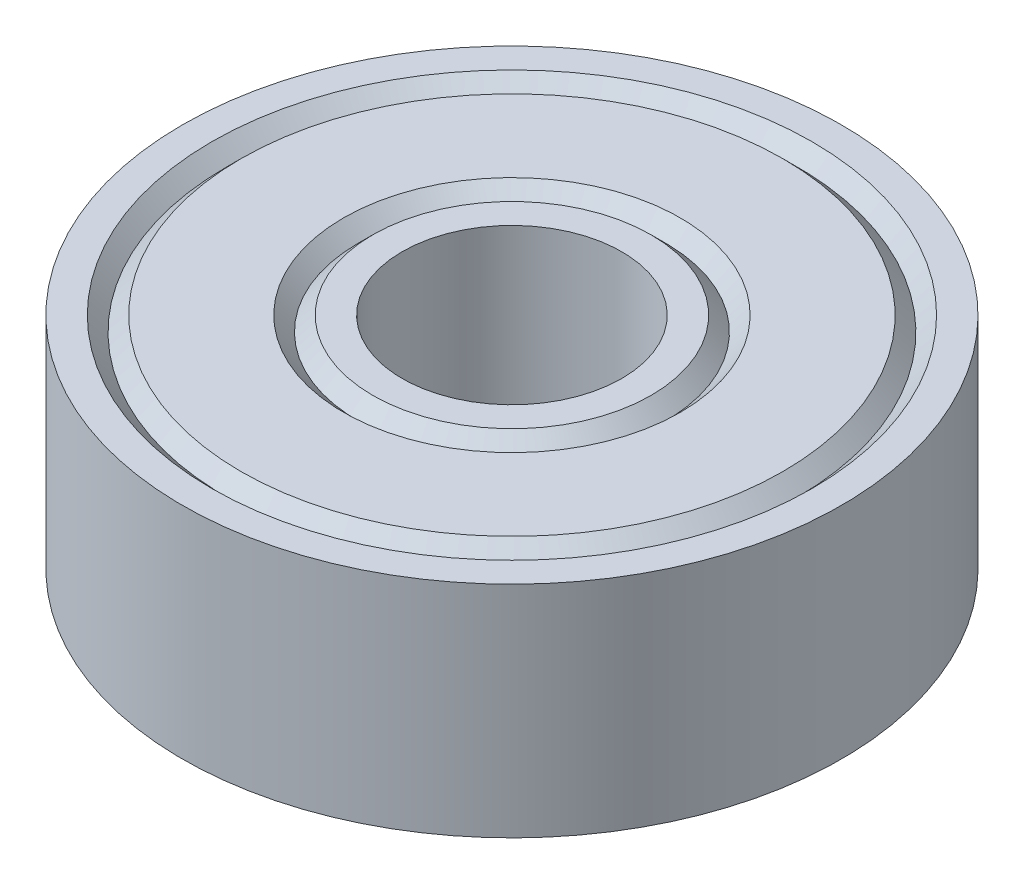
SolidWorks part; units mm, degrees
ref_plane "Front Plane" through (0, 0, 0) normal (0, 0, 1) x (1, 0, 0)
ref_plane "Top Plane" through (0, 0, 0) normal (0, 1, 0) x (1, 0, 0)
ref_plane "Right Plane" through (0, 0, 0) normal (1, 0, 0) x (0, 0, -1)
sketch "Sketch1" plane through (0, 0, 0) normal (0, 0, 1) x (1, 0, 0)
  line L0 (0, 4) -> (0, -4) construction
  line L1 (-4, 4) -> (-5.0667, 4)
  line L2 (-4, 4) -> (-4, -4)
  line L3 (-4, -4) -> (-5.0667, -4)
  line L4 (-12, 4) -> (-12, -4)
  line L5 (-10.9333, 4) -> (-10.4, 3.4667)
  line L6 (-10.4, 3.4667) -> (-9.8667, 4)
  line L7 (-6.1333, 4) -> (-5.6, 3.4667)
  line L8 (-5.6, 3.4667) -> (-5.0667, 4)
  line L9 (-10.9333, -4) -> (-10.4, -3.4667)
  line L10 (-10.4, -3.4667) -> (-9.8667, -4)
  line L11 (-6.1333, -4) -> (-5.6, -3.4667)
  line L12 (-5.6, -3.4667) -> (-5.0667, -4)
  line L13 (-6.1333, -4) -> (-9.8667, -4)
  line L14 (-10.9333, -4) -> (-12, -4)
  line L15 (-10.9333, 4) -> (-12, 4)
  line L16 (-6.1333, 4) -> (-9.8667, 4)
  line L17 (-10.4, 3.4667) -> (-5.6, 3.4667) construction
  line L18 (-10.4, 3.4667) -> (-10.4, -3.4667) construction
  line L19 (-5.6, -3.4667) -> (-10.4, -3.4667) construction
  line L20 (-5.6, 3.4667) -> (-5.6, -3.4667) construction
  line L21 (-10.4, 0) -> (-8.8, 0) construction
  line L22 (-5.0667, 4) -> (-6.1333, 4) construction
  line L23 (-8.8, 0) -> (-7.2, 0) construction
  line L24 (-10.4, 0) -> (-12, 0) construction
  line L25 (-7.2, 0) -> (-5.6, 0) construction
  line L26 (-5.6, 0) -> (-4, 0) construction
  dimension "D1" = 8
  dimension "D2" = 8
  dimension "D3" = 24
revolve "Revolve1" add sketch "Sketch1" angle 360 about L0
